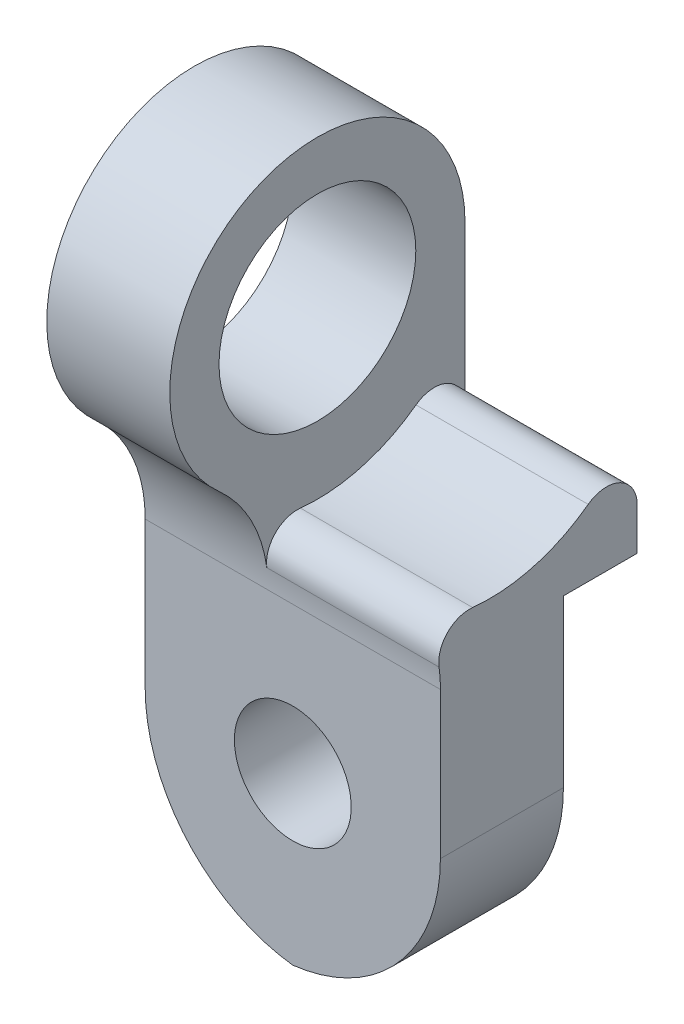
SolidWorks part; units mm, degrees
ref_plane "Front Plane" through (0, 0, 0) normal (0, 0, 1) x (1, 0, 0)
ref_plane "Top Plane" through (0, 0, 0) normal (0, 1, 0) x (1, 0, 0)
ref_plane "Right Plane" through (0, 0, 0) normal (1, 0, 0) x (0, 0, -1)
sketch "Sketch1" plane through (0, 0, 0) normal (-1, 0, 0) x (0, 1, 0)
  line L1 (-4.33, 1.2) -> (0, 1.2)
  line L2 (-4.33, 1.2) -> (-4.33, -0.4)
  line L3 (-4.33, -0.4) -> (-1.7889, -0.4)
  arc A0 (0, 1.2) -> (-0.8944, -0.8) centre (0, 0) cw
  circle A1 centre (0, 0) radius 0.8
  arc A3 (-1.7889, -0.4) -> (-0.8944, -0.8) centre (-1.7889, -1.6) cw
  dimension "D1" = 1.6
  dimension "D2" = 1.6
  dimension "D4" = 1.2
  dimension "D3" = 4.33
extrude "Boss-Extrude1" add sketch "Sketch1" along normal mid plane 1
sketch "Sketch2" plane through (0.5, 0, 0) normal (1, 0, 0) x (0, 0, -1)
  line L0 (1.2, 0) -> (1.2, -4.33) construction
  line L2 (1.2, -0.6185) -> (1.2, -4.33)
  line L3 (1.2, -4.33) -> (-0.4, -4.33)
  line L6 (0, -1.35) -> (0, -1.2) construction
  line L7 (-0.4, -4.33) -> (-0.4, -1.7889)
  arc A1 (1.2, -0.6185) -> (-0.5326, -1.2405) centre (0, 0) cw
  arc A2 (-0.4, -1.7889) -> (-0.5326, -1.2405) centre (-1.6, -1.7889) ccw
  arc A3 (-0.4, -1.7889) -> (-0.8, -0.8944) centre (-1.6, -1.7889) ccw construction
  circle A4 centre (0, 0) radius 1.2 construction
  arc A5 (1.2, 0) -> (-0.8, -0.8944) centre (0, 0) ccw construction
  dimension "D1" = 0.15
extrude "Boss-Extrude2" add sketch "Sketch2" along normal offset from surface (1.4 mm away) 2.4 up to face at (-0.5, -1.9516, -0.0411)
fillet "Fillet1" radius 0.25 2 edges at (1.2, -1.2405, 0.5326) (1.2, -0.6185, -1.2)
sketch "Sketch3" plane through (0, 0, -1.2) normal (0, 0, -1) x (-1, 0, 0)
  line L0 (0.5, 0) -> (0.5, -4.33) construction
  line L1 (-1.9, -4.33) -> (0.5, -4.33)
  line L2 (-1.9, -4.33) -> (-1.9, -1.63)
  line L3 (-1.9, -1.63) -> (0.5, -1.63)
  line L4 (0.5, -4.33) -> (0.5, -1.63)
  dimension "D1" = 2.7
extrude "Cut-Extrude1" cut sketch "Sketch3" against normal blind 0.6
hole_wizard "M1.2 Tapped Hole1" positions "Sketch4" profile "Sketch5" tap size "M1.2" standard "DIN" end condition through all
sketch "Sketch4" plane through (0, 0, -0.6) normal (0, 0, -1) x (-1, 0, 0)
  line L0 (-0.7, -1.63) -> (-0.7, -4.33) construction
  line L1 (0.5, -1.63) -> (-1.9, -1.63) construction
  line L2 (-1.9, -4.33) -> (0.5, -4.33) construction
  point P0 (-0.7, -2.98)
sketch "Sketch5" plane through (0.7, -2.98, -0.6) normal (1, 0, 0) x (0, 1, 0)
  line L0 (0, 0) -> (0, 1.8)
  line L1 (0, 1.8) -> (0.475, 1.8)
  line L2 (0.475, 1.8) -> (0.475, 0)
  line L5 (0.475, 0) -> (0, 0)
  line L11 (0, -6.35) -> (0, 107.95) construction
  dimension "Thru Tap Drill Dia." = 0.95
  dimension "Thru Tap Drill Depth" = 1.8
cosmetic thread "Hole Thread1" parameters "D2"=1.2
sketch "Sketch6" plane through (0, 0, -0.6) normal (0, 0, -1) x (-1, 0, 0)
  line L0 (-1.9, -2.98) -> (-1.9, -4.33)
  line L1 (-1.9, -1.63) -> (-1.9, -4.33) construction
  line L2 (-1.9, -4.33) -> (0.5, -4.33)
  line L3 (0.5, -4.33) -> (0.5, -2.98)
  line L4 (0.5, -4.33) -> (0.5, -1.63) construction
  arc A0 (-1.9, -2.98) -> (-0.7, -4.33) centre (-0.5406, -2.98) ccw
  arc A1 (0.5, -2.98) -> (-0.7, -4.33) centre (-0.8594, -2.98) cw
  line M2 (-1.9, -1.63) -> (-1.9, -4.33)
  line M3 (-1.9, -4.33) -> (0.5, -4.33)
  line M4 (0.5, -4.33) -> (0.5, -1.63)
extrude "Cut-Extrude2" cut sketch "Sketch6" against normal through all and the other way through all contours A0 M2 M3 | A1 L2 M4
